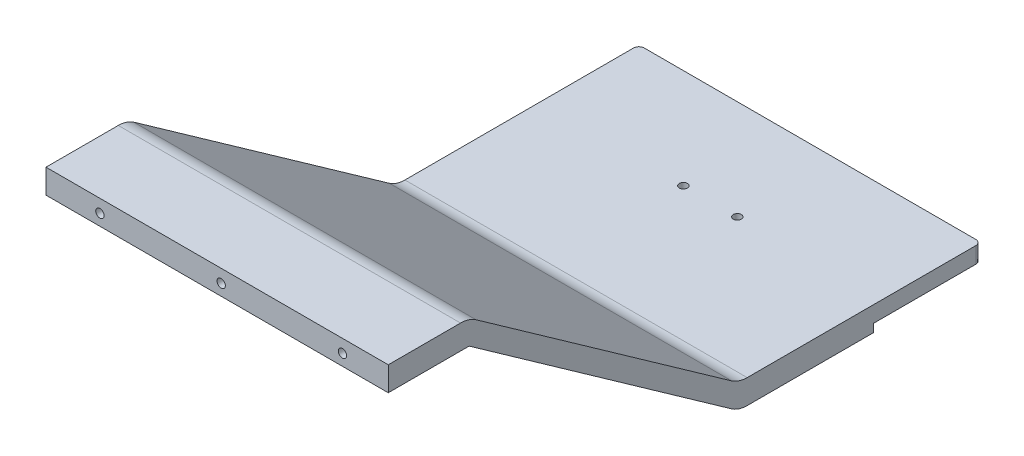
SolidWorks part; units mm, degrees
ref_plane "前视基准面" through (0, 0, 0) normal (0, 0, 1) x (1, 0, 0)
ref_plane "上视基准面" through (0, 0, 0) normal (0, 1, 0) x (1, 0, 0)
ref_plane "右视基准面" through (0, 0, 0) normal (1, 0, 0) x (0, 0, -1)
other "Configuration Table"
sketch "草图1" plane through (0, 0, 0) normal (0, 0, 1) x (1, 0, 0)
  line L0 (0, 0) -> (0, 79)
  line L1 (0, 79) -> (79, 79)
  line L2 (79, 79) -> (79, 70)
  line L3 (79, 70) -> (9, 70)
  line L4 (9, 70) -> (9, 0)
  line L5 (9, 0) -> (0, 0)
  dimension "D1" = 9
  dimension "D2" = 9
  dimension "D3" = 70
  dimension "D4" = 70
ref_plane "基准面1" through (0, 0, 100) normal (0, 0, 1) x (1, 0, 0)
sketch "草图2" plane through (0, 0, 100) normal (0, 0, 1) x (1, 0, 0)
  line L0 (0, 79) -> (-70.7107, 149.7107) construction
  line L1 (0, 0) -> (0, 79) construction
  line L2 (-70.7107, 149.7107) -> (-70.7107, 0)
  line L3 (-70.7107, 0) -> (-61.7107, 0)
  line L4 (-61.7107, 0) -> (-61.7107, 140.7107)
  line L5 (-61.7107, 140.7107) -> (79, 140.7107)
  line L6 (79, 140.7107) -> (79, 149.7107)
  line L7 (79, 149.7107) -> (-70.7107, 149.7107)
  line L8 (0, 0) -> (0, 79) construction
  line L9 (0, 79) -> (79, 79) construction
  dimension "D1" = 135
  dimension "D2" = 9
  dimension "D3" = 100
  dimension "D4" = 79
loft "放样1" add profiles "草图1", "草图2"
sketch "草图4" plane through (0, 0, 0) normal (0, 0, -1) x (-1, 0, 0)
  line L7 (-9, 0) -> (0, 0)
  line L8 (0, 0) -> (0, 79)
  line L9 (0, 79) -> (-79, 79)
  line L10 (-79, 79) -> (-79, 70)
  line L11 (-79, 70) -> (-77.7656, 70)
  line L12 (-77.7656, 70) -> (-9, 70)
  line L13 (-9, 70) -> (-9, 0)
  line L14 (-9, 0) -> (0, 0)
  line L15 (0, 0) -> (0, 79)
  line L16 (0, 79) -> (-79, 79)
  line L17 (-79, 79) -> (-79, 70)
  line L18 (-79, 70) -> (-77.7656, 70)
  line L19 (-77.7656, 70) -> (-9, 70)
  line L20 (-9, 70) -> (-9, 0)
  dimension "D1" = 0
extrude "凸台-拉伸1" add sketch "草图4" along normal blind 50
sketch "草图9" plane through (0, 0, -50) normal (0, 0, -1) x (-1, 0, 0)
  line L0 (-9, 70) -> (-9, 0) construction
  line L1 (-9, 70) -> (-55, 70)
  line L2 (-9, 70) -> (-9, 30)
  line L3 (-15, 64) -> (-55, 64)
  line L4 (-55, 70) -> (-55, 64)
  line L6 (-15, 64) -> (-15, 30)
  line L7 (-15, 30) -> (-9, 30)
  dimension "D1" = 6
  dimension "D2" = 46
  dimension "D3" = 6
  dimension "D4" = 40
extrude "凸台-拉伸3" add sketch "草图9" against normal blind 6
fillet "圆角1" radius 10 7 edges
sketch "草图11" plane through (0, 0, -44) normal (0, 0, 1) x (1, 0, 0)
  circle A0 centre (12, 45) radius 1.55
  circle A1 centre (12, 65) radius 1.55
  circle A2 centre (30, 67) radius 1.55
  circle A3 centre (50, 67) radius 1.55
  dimension "D1" = 3.1
extrude "切除-拉伸1" cut sketch "草图11" against normal through all
sketch "草图12" plane through (0, 0, -50) normal (0, 0, -1) x (-1, 0, 0)
  line L0 (0, 19) -> (0, 0)
  line L1 (0, 0) -> (0, 69) construction
  line L2 (0, 0) -> (-6, 0)
  line L3 (-9, 0) -> (0, 0) construction
  line L5 (-6, 0) -> (-6, 19)
  line L6 (0, 19) -> (-6, 19)
  line L7 (-2.9289, 76.0711) -> (-93.7798, -14.7798) construction
  line L8 (0, 0) -> (0, 69) construction
  line L9 (-60, 79) -> (-60, 73)
  line L10 (-79, 73) -> (-60, 73)
  line L11 (-79, 79) -> (-79, 73)
  line L12 (-60, 79) -> (-79, 79)
  arc A0 (0, 69) -> (-10, 79) centre (-10, 69) ccw construction
  dimension "D1" = 19
  dimension "D2" = 6
  dimension "D3" = 45
extrude "凸台-拉伸4" add sketch "草图12" along normal blind 40
fillet "圆角2" radius 2 9 edges at (3, 0, -90) (3, 19, -90) (9, 30, -47) (15, 30, -47) (15, 64, -47) (55, 70, -47) (55, 64, -47) (79, 76, -90) (60, 76, -90)
sketch "草图13" plane through (79, 0, 0) normal (1, 0, 0) x (0, 0, -1)
  line L0 (90, 79) -> (88, 79) construction
  line L1 (90, 79) -> (90, 73) construction
  line L9 (50, 73) -> (88, 73)
  line L10 (88, 73) -> (88, 79)
  line L11 (88, 79) -> (3.1784, 79)
  line L12 (-2.5951, 80.835) -> (-100, 149.7107)
  line L13 (-100, 149.7107) -> (-100, 149.2162)
  line L14 (-100, 149.2162) -> (-100, 140.7107)
  line L15 (-100, 140.7107) -> (-2.5951, 71.835)
  line L16 (3.1784, 70) -> (50, 70)
  line L17 (50, 70) -> (50, 73)
  line L18 (50, 73) -> (90, 73)
  line L19 (90, 73) -> (90, 79)
  line L20 (90, 79) -> (3.1784, 79)
  line L21 (-2.5951, 80.835) -> (-100, 149.7107)
  line L22 (-100, 149.7107) -> (-100, 149.2162)
  line L23 (-100, 149.2162) -> (-100, 140.7107)
  line L24 (-100, 140.7107) -> (-2.5951, 71.835)
  line L25 (3.1784, 70) -> (50, 70)
  line L26 (50, 70) -> (50, 73)
  arc A2 (-2.5951, 80.835) -> (3.1784, 79) centre (3.1784, 89) ccw
  arc A3 (-2.5951, 71.835) -> (3.1784, 70) centre (3.1784, 80) ccw
  arc A4 (-2.5951, 80.835) -> (3.1784, 79) centre (3.1784, 89) ccw
  arc A5 (-2.5951, 71.835) -> (3.1784, 70) centre (3.1784, 80) ccw
  dimension "D1" = 0
extrude "凸台-拉伸5" add sketch "草图13" along normal blind 127 separate body
delete or keep bodies "实体-删除/保留 1" type delete bodies bodies 112
sketch "草图14" plane through (0, 0, 100) normal (0, 0, 1) x (1, 0, 0)
  line L4 (79, 149.7107) -> (79, 140.7107)
  line L5 (79, 140.7107) -> (206, 140.7107)
  line L6 (206, 140.7107) -> (206, 149.7107)
  line L7 (206, 149.7107) -> (79, 149.7107)
  line L8 (79, 149.7107) -> (79, 140.7107)
  line L9 (79, 140.7107) -> (206, 140.7107)
  line L10 (206, 140.7107) -> (206, 149.7107)
  line L11 (206, 149.7107) -> (79, 149.7107)
  dimension "D1" = 0
extrude "凸台-拉伸6" add sketch "草图14" along normal blind 30
sketch "草图15" plane through (0, 0, 130) normal (0, 0, 1) x (1, 0, 0)
  line L0 (79, 149.7107) -> (79, 140.7107) construction
  line L1 (79, 140.7107) -> (206, 140.7107) construction
  circle A0 centre (99, 144.8907) radius 1.55
  circle A1 centre (144, 144.8907) radius 1.55
  circle A2 centre (189, 144.8907) radius 1.55
  dimension "D1" = 3.1
  dimension "D2" = 20
  dimension "D3" = 4.18
  dimension "D5" = 45
  dimension "D4" = 3
extrude "切除-拉伸2" cut sketch "草图15" against normal blind 5
fillet "圆角3" radius 2 2 edges at (79, 76, -90) (206, 76, -90)
sketch "草图16" plane through (0, 73, 0) normal (0, -1, 0) x (1, 0, 0)
  line L1 (142.5, 130) -> (142.5, 82.7932) construction
  line L2 (79, 130) -> (206, 130) construction
  line L3 (206, -50) -> (79, -50) construction
  circle A0 centre (132.5, -53) radius 1.5
  circle A1 centre (152.5, -53) radius 1.5
  dimension "D1" = 3
  dimension "D2" = 3
  dimension "D3" = 20
extrude "切除-拉伸3" cut sketch "草图16" against normal through all
fillet "圆角4" radius 10 1 edges at (142.5, 149.7107, 100)
